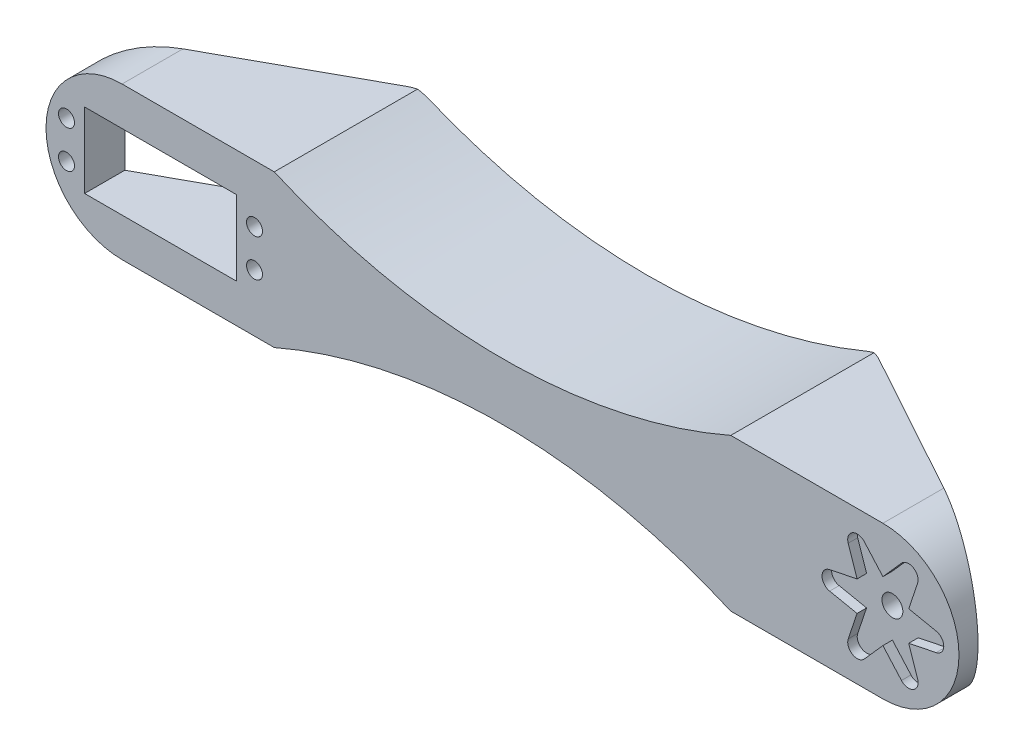
SolidWorks part; units mm, degrees
ref_plane "Front Plane" through (0, 0, 0) normal (0, 0, 1) x (1, 0, 0)
ref_plane "Top Plane" through (0, 0, 0) normal (0, 1, 0) x (1, 0, 0)
ref_plane "Right Plane" through (0, 0, 0) normal (1, 0, 0) x (0, 0, -1)
sketch "Sketch1" plane through (0, 0, 0) normal (0, 0, 1) x (1, 0, 0)
  line L0 (-79.0738, 18.5935) -> (120.9262, 18.5935) construction
  line L1 (-79.0738, 38.5935) -> (120.9262, 38.5935)
  line L2 (-79.0738, -1.4065) -> (120.9262, -1.4065)
  arc A0 (-79.0738, 38.5935) -> (-79.0738, -1.4065) centre (-79.0738, 18.5935) ccw
  arc A1 (120.9262, -1.4065) -> (120.9262, 38.5935) centre (120.9262, 18.5935) ccw
  circle A2 centre (-79.0738, 18.5935) radius 2.7394
  circle A3 centre (120.9262, 18.5935) radius 2.7394
  point P2 (20.9262, 18.5935)
  dimension "D1" = 200
  dimension "D2" = 20
extrude "Boss-Extrude1" add sketch "Sketch1" along normal blind 60
sketch "Sketch16" plane through (0, 0, 60) normal (0, 0, 1) x (1, 0, 0)
  line L0 (-88.9238, 28.4435) -> (-49.0238, 28.4435)
  line L1 (-88.6238, 28.4435) -> (-94.9738, 28.4435) construction
  line L2 (-42.9738, 28.4435) -> (-49.3238, 28.4435) construction
  line L3 (-49.0238, 28.4435) -> (-49.0238, 8.7435)
  line L4 (-49.3238, 8.7435) -> (-42.9738, 8.7435) construction
  line L5 (-49.0238, 8.7435) -> (-88.9238, 8.7435)
  line L6 (-94.9738, 8.7435) -> (-88.6238, 8.7435) construction
  line L7 (-88.9238, 8.7435) -> (-88.9238, 28.4435)
  circle A0 centre (-93.6849, 23.5185) radius 2.1
  circle A1 centre (-93.6849, 13.6685) radius 2.1
  circle A2 centre (-44.2626, 23.5185) radius 2.1
  circle A3 centre (-44.2626, 13.6685) radius 2.1
extrude "Cut-Extrude9" cut sketch "Sketch16" against normal through all
sketch "Sketch18" plane through (0, -1.4065, 0) normal (0, -1, 0) x (-1, 0, 0)
  line L1 (-140.9262, 0) -> (-140.9262, -60) construction
  line L2 (-140.9262, -55) -> (-140.9262, 0)
  line L5 (99.0738, -60) -> (99.0738, 0) construction
  line L6 (99.0738, -55) -> (99.0738, 0)
  line L8 (-140.9262, 0) -> (-40.9262, 0)
  line L9 (79.0738, 0) -> (-120.9262, 0) construction
  line L10 (99.0738, 0) -> (-0.9262, 0)
  line L11 (-40.9262, 0) -> (-140.9262, -55)
  line L12 (-0.9262, 0) -> (99.0738, -55)
  dimension "D1" = 55
  dimension "D2" = 55
  dimension "D3" = 100
  dimension "D4" = 100
  dimension "D5" = 114.1271
  dimension "D6" = 114.1271
extrude "Cut-Extrude11" cut sketch "Sketch18" against normal through all
sketch "Sketch19" plane through (0, -1.4065, 0) normal (0, -1, 0) x (-1, 0, 0)
  line L1 (-120.9262, -44) -> (-40.9262, 0) construction
  line L3 (42.1626, 0) -> (-80.9262, 0)
  line L4 (-80.9262, 0) -> (-80.9262, -22)
  line L5 (42.1626, 0) -> (42.1626, -22)
  line L6 (42.1626, -22) -> (-80.9262, -22)
extrude "Cut-Extrude12" cut sketch "Sketch19" against normal through all
sketch "Sketch22" plane through (0, 0, 22) normal (0, 0, -1) x (-1, 0, 0)
  line L0 (-80.9262, 38.5935) -> (39.0738, 38.5935)
  line L1 (-80.9262, -1.4065) -> (39.0738, -1.4065)
  arc A0 (-80.9262, 38.5935) -> (39.0738, 38.5935) centre (-20.9262, 176.0708) ccw
  arc A1 (-80.9262, -1.4065) -> (39.0738, -1.4065) centre (-20.9262, -138.8838) cw
extrude "Cut-Extrude14" cut sketch "Sketch22" against normal through all
fillet "Fillet3" radius 10 1 edges at (80.9262, 18.5935, 22)
fillet "Fillet4" radius 10 1 edges at (-39.0738, 18.5935, 22)
sketch "Sketch23" plane through (0, 0, 60) normal (0, 0, 1) x (1, 0, 0)
  line L0 (116.0471, 31.9431) -> (120.9262, 26.4384)
  line L1 (120.9262, 26.4384) -> (125.8054, 31.9431)
  line L2 (130.0478, 29.4937) -> (127.7202, 22.516)
  line L3 (127.7202, 22.516) -> (134.9269, 21.0428)
  line L4 (134.9269, 16.1441) -> (127.7202, 14.671)
  line L5 (127.7202, 14.671) -> (130.0478, 7.6932)
  line L6 (125.8054, 5.2439) -> (120.9262, 10.7485)
  line L7 (120.9262, 10.7485) -> (116.0471, 5.2439)
  line L8 (111.8047, 7.6932) -> (114.1323, 14.671)
  line L9 (114.1323, 14.671) -> (106.9256, 16.1441)
  line L10 (106.9256, 21.0428) -> (114.1323, 22.516)
  line L11 (114.1323, 22.516) -> (111.8047, 29.4937)
  arc A0 (111.8047, 29.4937) -> (116.0471, 31.9431) centre (114.1762, 30.2848) cw
  arc A1 (125.8054, 31.9431) -> (130.0478, 29.4937) centre (127.6762, 30.2848) cw
  arc A2 (134.9269, 21.0428) -> (134.9269, 16.1441) centre (134.4262, 18.5935) cw
  arc A3 (130.0478, 7.6932) -> (125.8054, 5.2439) centre (127.6762, 6.9021) cw
  arc A4 (116.0471, 5.2439) -> (111.8047, 7.6932) centre (114.1762, 6.9021) cw
  arc A5 (106.9256, 16.1441) -> (106.9256, 21.0428) centre (107.4262, 18.5935) cw
extrude "Cut-Extrude15" cut sketch "Sketch23" against normal blind 2.5
